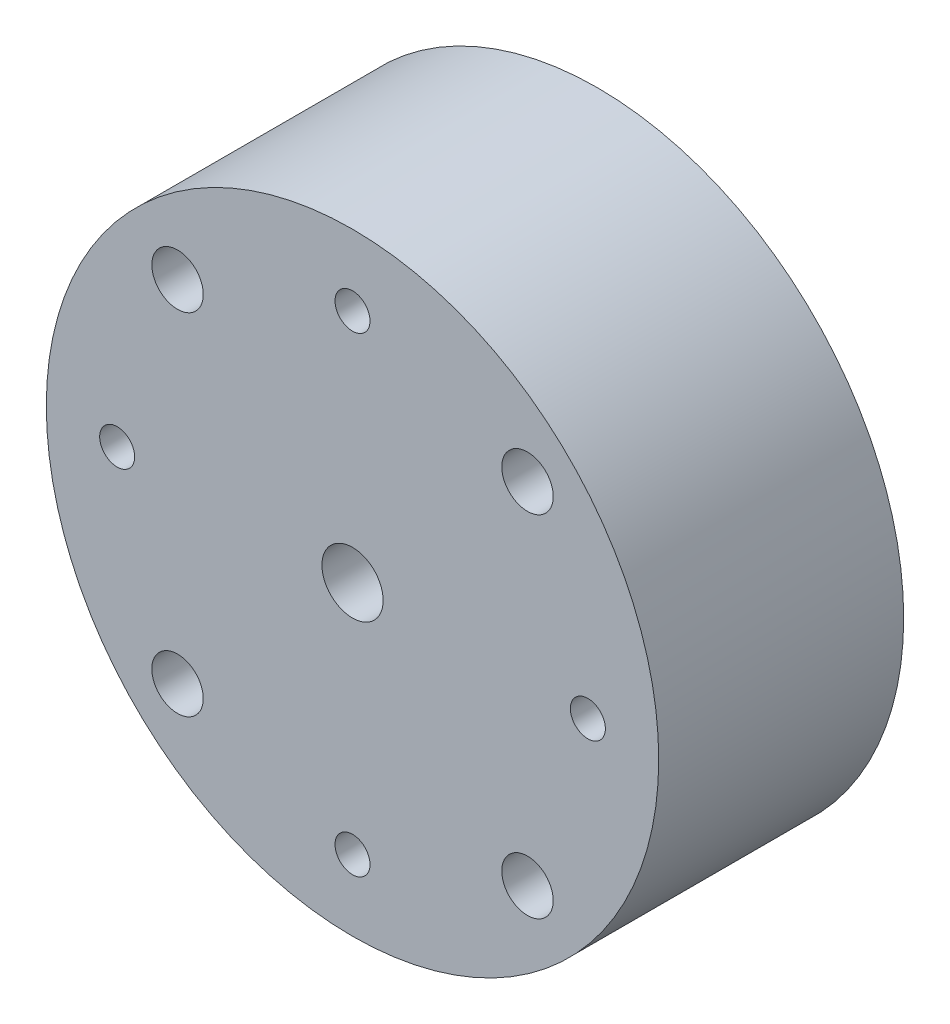
SolidWorks part; units mm, degrees
ref_plane "Front Plane" through (0, 0, 0) normal (0, 0, 1) x (1, 0, 0)
ref_plane "Top Plane" through (0, 0, 0) normal (0, 1, 0) x (1, 0, 0)
ref_plane "Right Plane" through (0, 0, 0) normal (1, 0, 0) x (0, 0, -1)
sketch "Sketch1" plane through (0, 0, 0) normal (0, 0, 1) x (1, 0, 0)
  circle A0 centre (0, 0) radius 17.5
  circle A1 centre (0, 0) radius 1.75
  dimension "D1" = 35
  dimension "D2" = 3.5
extrude "Boss-Extrude1" add sketch "Sketch1" along normal blind 14
sketch "Sketch2" plane through (0, 0, 14) normal (0, 0, 1) x (1, 0, 0)
  circle A0 centre (0, 13.45) radius 1
  dimension "D1" = 2
  dimension "D2" = 13.45
extrude "Cut-Extrude1" cut sketch "Sketch2" against normal through all
pattern_circular "CirPattern1" count 4 over 360 about axis through (0, 0, 0) along (0, 0, 1) of "Cut-Extrude1"
sketch "Sketch3" plane through (0, 0, 14) normal (0, 0, 1) x (1, 0, 0)
  line L0 (-10, 0) -> (-10, -10) construction
  line L1 (0, 0) -> (-17.5, 0) construction
  circle A0 centre (-10, -10) radius 1.47
  circle A3 centre (0, 0) radius 17.5 construction
  dimension "D1" = 2.94
  dimension "D2" = 10
  dimension "D3" = 10
extrude "Cut-Extrude2" cut sketch "Sketch3" against normal through all
pattern_circular "CirPattern2" count 4 over 360 about axis through (0, 0, 0) along (0, 0, 1) of "Cut-Extrude2"
